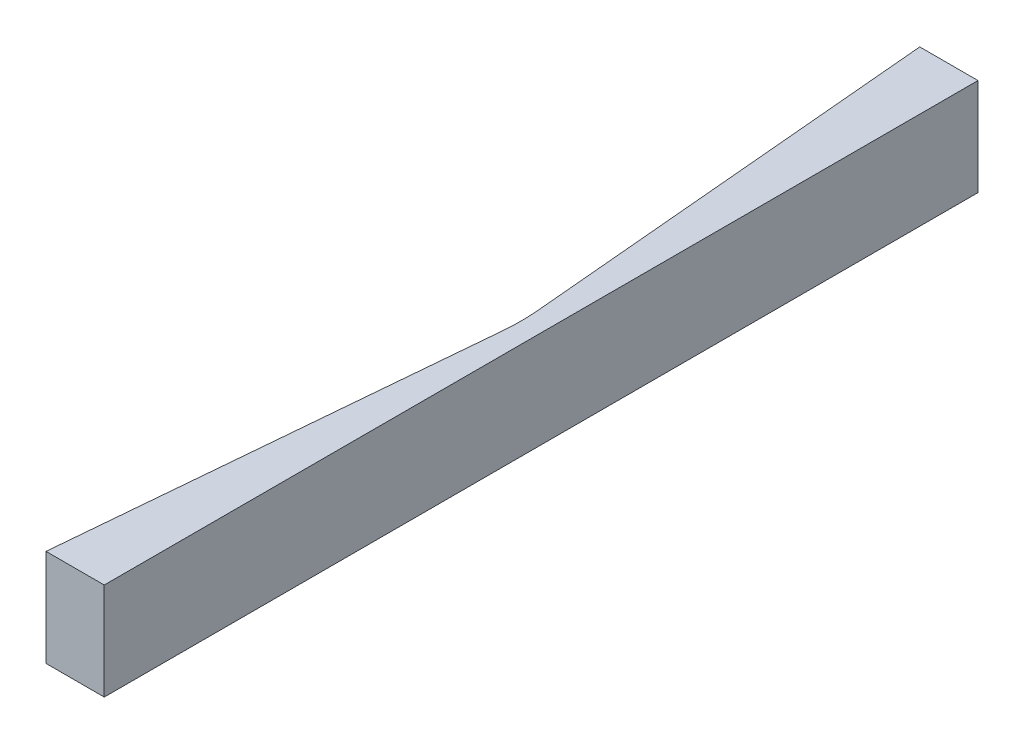
SolidWorks part; units mm, degrees
ref_plane "Alzado" through (0, 0, 0) normal (0, 0, 1) x (1, 0, 0)
ref_plane "Planta" through (0, 0, 0) normal (0, 1, 0) x (1, 0, 0)
ref_plane "Vista lateral" through (0, 0, 0) normal (1, 0, 0) x (0, 0, -1)
sketch "Croquis1" plane through (0, 0, 0) normal (0, 1, 0) x (1, 0, 0)
  line L0 (0, 0) -> (-3, 0)
  line L1 (-3, 0) -> (-1, 22.5)
  line L2 (-1, 22.5) -> (-3, 45)
  line L3 (-3, 45) -> (0, 45)
  line L4 (0, 45) -> (0, 0)
  point P5 (-4, 70.7734)
  point P7 (0, 0)
  point P8 (-1.9573, 22.5)
  dimension "D1" = 3
  dimension "D2" = 45
  dimension "D3" = 1
extrude "Saliente-Extruir1" add sketch "Croquis1" along normal blind 5
fillet "Redondeo1" radius 10 1 edges at (-1, 2.5, -22.5)
